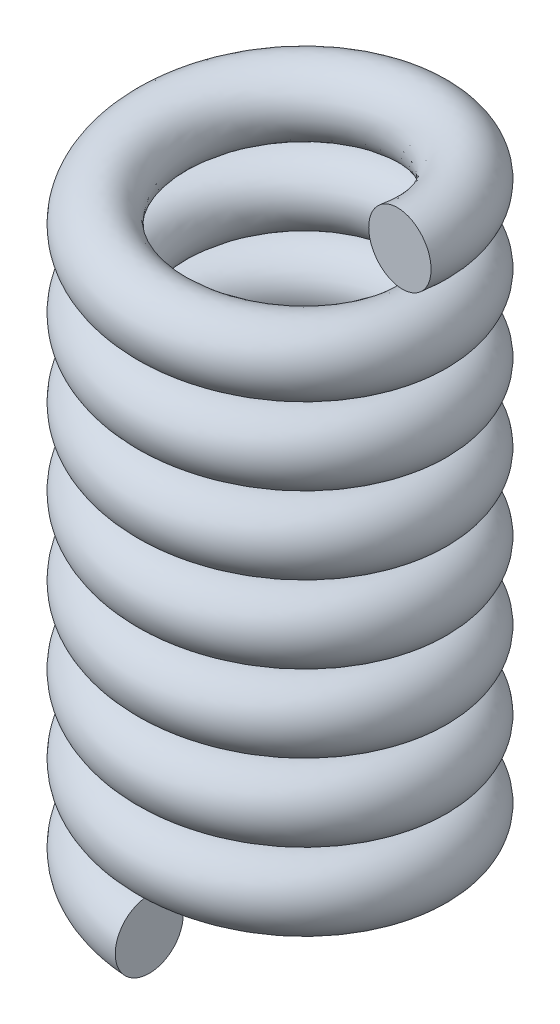
SolidWorks part; units mm, degrees
material "1.8159 (51CrV4)"
ref_plane "E_Oben" through (0, 0, 0) normal (0, 0, 1) x (1, 0, 0)
ref_plane "E_Vorne" through (0, 0, 0) normal (0, 1, 0) x (1, 0, 0)
ref_plane "E_Rechts" through (0, 0, 0) normal (1, 0, 0) x (0, 0, -1)
sketch "Skizze4" plane through (0, 0, 0) normal (0, 1, 0) x (1, 0, 0)
  circle A0 centre (0, 0) radius 50
  dimension "D1" = 100
curve "Spirale/Helix1" pitch 29.5 height 229 turns 7.7627
sketch "Skizze5" plane through (0, 0, 0) normal (1, 0, 0) x (0, 0, -1)
  line L2 (55, 0) -> (-55, 0) construction
  circle A1 centre (-50, 0) radius 13
  spline S0 degree 3 poles (-50, 0) (-50, 0.3123) (-49.3318, 0.9388) (-46.3649, 1.877) (-41.5514, 2.8156) (-35.0832, 3.7541) (-27.2177, 4.6926) (-18.2683, 5.6311) (-8.5913, 6.5697) (1.4278, 7.5082) (11.39, 8.4467) (20.8986, 9.3852) (29.575, 10.3238) (37.0735, 11.2623) (43.0955, 12.2008) (47.4012, 13.1393) (49.8192, 14.0779) (50.2531, 15.0164) (48.6856, 15.9549) (45.1793, 16.8934) (39.8736, 17.832) (32.9799, 18.7705) (24.7728, 19.709) (15.5792, 20.6475) (5.765, 21.5861) (-4.2787, 22.5246) (-14.152, 23.4631) (-23.4617, 24.4016) (-31.8371, 25.3402) (-38.9445, 26.2787) (-44.5009, 27.2172) (-48.2851, 28.1557) (-50.1463, 29.0943) (-50.0104, 30.0328) (-47.8828, 30.9713) (-43.8482, 31.9098) (-38.0674, 32.8484) (-30.7706, 33.7869) (-22.2482, 34.7254) (-12.8399, 35.6639) (-2.9202, 36.6025) (7.1158, 37.541) (16.8685, 38.4795) (25.9493, 39.418) (33.9967, 40.3566) (40.6901, 41.2951) (45.7631, 42.2336) (49.0135, 43.1721) (50.3119, 44.1107) (49.6067, 45.0492) (46.9258, 45.9877) (42.3761, 46.9262) (36.1387, 47.8648) (28.4622, 48.8033) (19.652, 49.7418) (10.0593, 50.6803) (0.0659, 51.6189) (-9.9301, 52.5574) (-19.5306, 53.4959) (-28.3533, 54.4344) (-36.0469, 55.373) (-42.3048, 56.3115) (-46.878, 57.25) (-49.5842, 58.1885) (-50.3157, 59.127) (-49.0433, 60.0656) (-45.8178, 61.0041) (-40.7676, 61.9426) (-34.0938, 62.8811) (-26.0621, 63.8197) (-16.9926, 64.7582) (-7.2463, 65.6967) (2.7886, 66.6352) (12.7124, 67.5738) (22.1299, 68.5123) (30.6661, 69.4508) (37.9811, 70.3893) (43.7834, 71.3279) (47.842, 72.2664) (49.9953, 73.2049) (50.1575, 74.1434) (48.3221, 75.082) (44.5623, 76.0205) (39.0278, 76.959) (31.939, 77.8975) (23.5783, 78.8361) (14.2785, 79.7746) (4.41, 80.7131) (-5.6341, 81.6516) (-15.4538, 82.5902) (-24.658, 83.5287) (-32.8802, 84.4672) (-39.793, 85.4057) (-45.121, 86.3443) (-48.652, 87.2828) (-50.2455, 88.2213) (-49.8378, 89.1598) (-47.4454, 90.0984) (-43.1635, 91.0369) (-37.1625, 91.9754) (-29.6815, 92.9139) (-21.0185, 93.8525) (-11.5184, 94.791) (-1.5595, 95.7295) (8.4614, 96.668) (18.1454, 97.6066) (27.1067, 98.5451) (34.9885, 99.4836) (41.4769, 100.4221) (46.3134, 101.3607) (49.3055, 102.2992) (50.3339, 103.2377) (49.3578, 104.1762) (46.416, 105.1148) (41.6257, 106.0533) (35.1776, 106.9918) (27.3285, 107.9303) (18.3911, 108.8689) (8.7212, 109.8074) (-1.296, 110.7459) (-11.2616, 111.6844) (-20.7787, 112.623) (-29.4682, 113.5615) (-36.9842, 114.5) (-43.0273, 115.4385) (-47.3567, 116.377) (-49.8002, 117.3156) (-50.2604, 118.2541) (-48.7189, 119.1926) (-45.2372, 120.1311) (-39.9539, 121.0697) (-33.0794, 122.0082) (-24.8875, 122.9467) (-15.7044, 123.8852) (-5.896, 124.8238) (4.1473, 125.7623) (14.0255, 126.7008) (23.345, 127.6393) (31.7349, 128.5779) (38.8608, 129.5164) (44.4392, 130.4549) (48.2477, 131.3934) (50.1347, 132.332) (50.0251, 133.2705) (47.9232, 134.209) (43.9128, 135.1475) (38.1535, 136.0861) (30.8748, 137.0246) (22.3664, 137.9631) (12.9673, 138.9016) (3.0517, 139.8402) (-6.9853, 140.7787) (-16.7442, 141.7172) (-25.8363, 142.6557) (-33.8994, 143.5943) (-40.6124, 144.5328) (-45.708, 145.4713) (-48.9833, 146.4098) (-50.3078, 147.3484) (-49.6288, 148.2869) (-46.9733, 149.2254) (-42.4471, 150.1639) (-36.2304, 151.1025) (-28.5708, 152.041) (-19.7733, 152.9795) (-10.1884, 153.918) (-0.1977, 154.8566) (9.8008, 155.7951) (19.4091, 156.7336) (28.2443, 157.6721) (35.9548, 158.6107) (42.2333, 159.5492) (46.8298, 160.4877) (49.5613, 161.4262) (50.3191, 162.3648) (49.0728, 163.3033) (45.8722, 164.2418) (40.8447, 165.1803) (34.1906, 166.1189) (26.1748, 167.0574) (17.1166, 167.9959) (7.3767, 168.9344) (-2.657, 169.873) (-12.5848, 170.8115) (-22.0115, 171.75) (-30.5615, 172.6885) (-37.8944, 173.627) (-43.7182, 174.5656) (-47.8009, 175.5041) (-49.9798, 176.4426) (-50.1683, 177.3811) (-48.3589, 178.3197) (-44.6235, 179.2582) (-39.1109, 180.1967) (-32.0408, 181.1352) (-23.6946, 182.0738) (-14.4048, 183.0123) (-4.5413, 183.9508) (5.5031, 184.8893) (15.3283, 185.8279) (24.543, 186.7664) (32.7803, 187.7049) (39.7122, 188.6434) (45.0624, 189.582) (48.6181, 190.5205) (50.2375, 191.459) (49.8561, 192.3975) (47.4893, 193.3361) (43.2311, 194.2746) (37.2513, 195.2131) (29.7879, 196.1516) (21.1382, 197.0902) (11.6466, 198.0287) (1.6913, 198.9672) (-8.3315, 199.9057) (-18.0224, 200.8443) (-26.9956, 201.7828) (-34.8936, 202.7213) (-41.4021, 203.6598) (-46.2616, 204.5984) (-49.2788, 205.5369) (-50.3334, 206.4754) (-49.3835, 207.4139) (-46.4668, 208.3525) (-41.6996, 209.291) (-35.2717, 210.2295) (-27.4391, 211.168) (-18.5137, 212.1066) (-8.851, 213.0451) (1.1642, 213.9836) (11.1331, 214.9221) (20.6585, 215.8607) (29.3613, 216.7992) (36.8947, 217.7377) (42.9587, 218.6762) (47.3119, 219.6148) (49.7809, 220.5533) (50.2674, 221.4918) (48.7519, 222.4303) (45.2948, 223.3689) (40.0339, 224.3074) (33.1786, 225.2459) (25.0022, 226.1844) (15.8289, 227.123) (6.0294, 228.0612) (-0.6738, 228.6877) (-3.9893, 229) knots 0 0 0 0 0.004098 0.008197 0.012295 0.016393 0.020492 0.02459 0.028689 0.032787 0.036885 0.040984 0.045082 0.04918 0.053279 0.057377 0.061475 0.065574 0.069672 0.07377 0.077869 0.081967 0.086066 0.090164 0.094262 0.098361 0.102459 0.106557 0.110656 0.114754 0.118852 0.122951 0.127049 0.131148 0.135246 0.139344 0.143443 0.147541 0.151639 0.155738 0.159836 0.163934 0.168033 0.172131 0.17623 0.180328 0.184426 0.188525 0.192623 0.196721 0.20082 0.204918 0.209016 0.213115 0.217213 0.221311 0.22541 0.229508 0.233607 0.237705 0.241803 0.245902 0.25 0.254098 0.258197 0.262295 0.266393 0.270492 0.27459 0.278689 0.282787 0.286885 0.290984 0.295082 0.29918 0.303279 0.307377 0.311475 0.315574 0.319672 0.32377 0.327869 0.331967 0.336066 0.340164 0.344262 0.348361 0.352459 0.356557 0.360656 0.364754 0.368852 0.372951 0.377049 0.381148 0.385246 0.389344 0.393443 0.397541 0.401639 0.405738 0.409836 0.413934 0.418033 0.422131 0.42623 0.430328 0.434426 0.438525 0.442623 0.446721 0.45082 0.454918 0.459016 0.463115 0.467213 0.471311 0.47541 0.479508 0.483607 0.487705 0.491803 0.495902 0.5 0.504098 0.508197 0.512295 0.516393 0.520492 0.52459 0.528689 0.532787 0.536885 0.540984 0.545082 0.54918 0.553279 0.557377 0.561475 0.565574 0.569672 0.57377 0.577869 0.581967 0.586066 0.590164 0.594262 0.598361 0.602459 0.606557 0.610656 0.614754 0.618852 0.622951 0.627049 0.631148 0.635246 0.639344 0.643443 0.647541 0.651639 0.655738 0.659836 0.663934 0.668033 0.672131 0.67623 0.680328 0.684426 0.688525 0.692623 0.696721 0.70082 0.704918 0.709016 0.713115 0.717213 0.721311 0.72541 0.729508 0.733607 0.737705 0.741803 0.745902 0.75 0.754098 0.758197 0.762295 0.766393 0.770492 0.77459 0.778689 0.782787 0.786885 0.790984 0.795082 0.79918 0.803279 0.807377 0.811475 0.815574 0.819672 0.82377 0.827869 0.831967 0.836066 0.840164 0.844262 0.848361 0.852459 0.856557 0.860656 0.864754 0.868852 0.872951 0.877049 0.881148 0.885246 0.889344 0.893443 0.897541 0.901639 0.905738 0.909836 0.913934 0.918033 0.922131 0.92623 0.930328 0.934426 0.938525 0.942623 0.946721 0.95082 0.954918 0.959016 0.963115 0.967213 0.971311 0.97541 0.979508 0.983607 0.987705 0.991803 0.995902 1 1 1 1 construction
  dimension "D1" = 26
sweep "Austragung2" add profiles "Skizze5" path "Spirale/Helix1"
